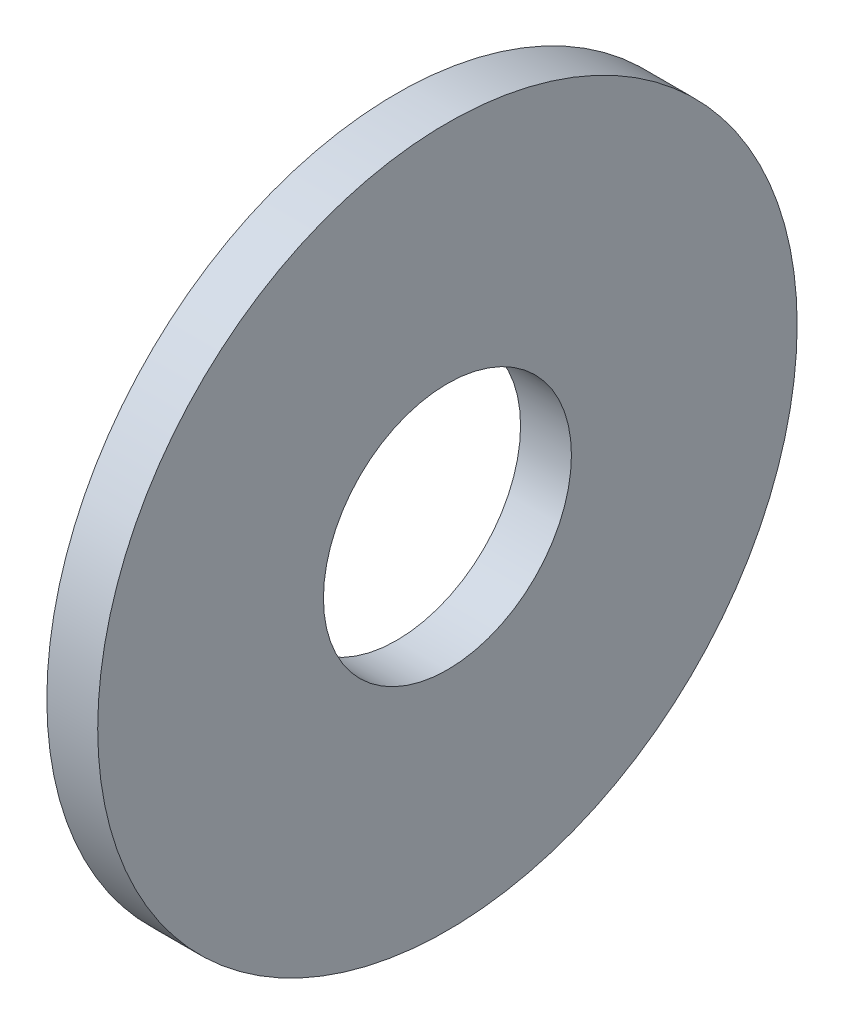
SolidWorks part; units mm, degrees
ref_plane "Plane1" through (0, 0, 0) normal (0, 0, 1) x (1, 0, 0)
ref_plane "Plane2" through (0, 0, 0) normal (0, 1, 0) x (1, 0, 0)
ref_plane "Plane3" through (0, 0, 0) normal (1, 0, 0) x (0, 0, -1)
sketch "Sketch1" plane through (0, 0, 0) normal (0, 0, 1) x (1, 0, 0)
  line L0 (-34.925, 0) -> (9.525, 0) construction
  line L1 (0, 19.5) -> (0, 55)
  line L2 (0, 55) -> (-8, 55)
  line L3 (-8, 55) -> (-8, 19.5)
  line L4 (-8, 19.5) -> (0, 19.5)
  dimension "Thickness" = 8
  dimension "Inside_dia" = 39
  dimension "Outside_dia" = 110
revolve "Base-Revolve" add sketch "Sketch1" angle 360 about L0
